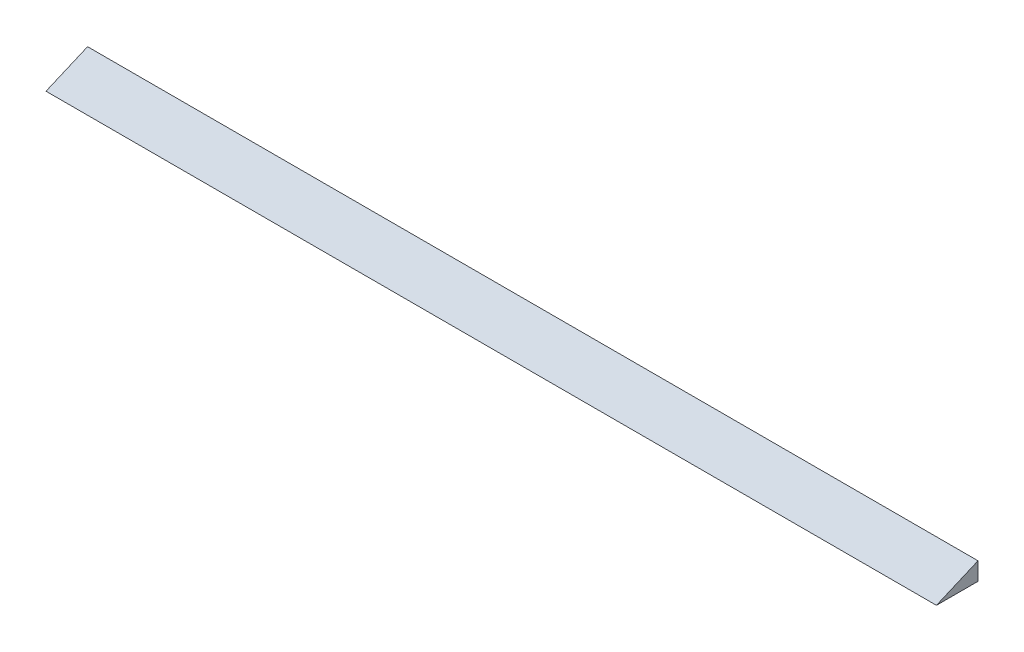
SolidWorks part; units mm, degrees
ref_plane "정면" through (0, 0, 0) normal (0, 0, 1) x (1, 0, 0)
ref_plane "윗면" through (0, 0, 0) normal (0, 1, 0) x (1, 0, 0)
ref_plane "우측면" through (0, 0, 0) normal (1, 0, 0) x (0, 0, -1)
sketch "스케치1" plane through (0, 0, 0) normal (1, 0, 0) x (0, 0, -1)
  line L0 (0, 0) -> (0, 3)
  line L1 (0, 3) -> (-7, 0)
  line L2 (-7, 0) -> (0, 0)
  dimension "D1" = 3
  dimension "D2" = 7
extrude "보스-돌출1" add sketch "스케치1" along normal mid plane 150
